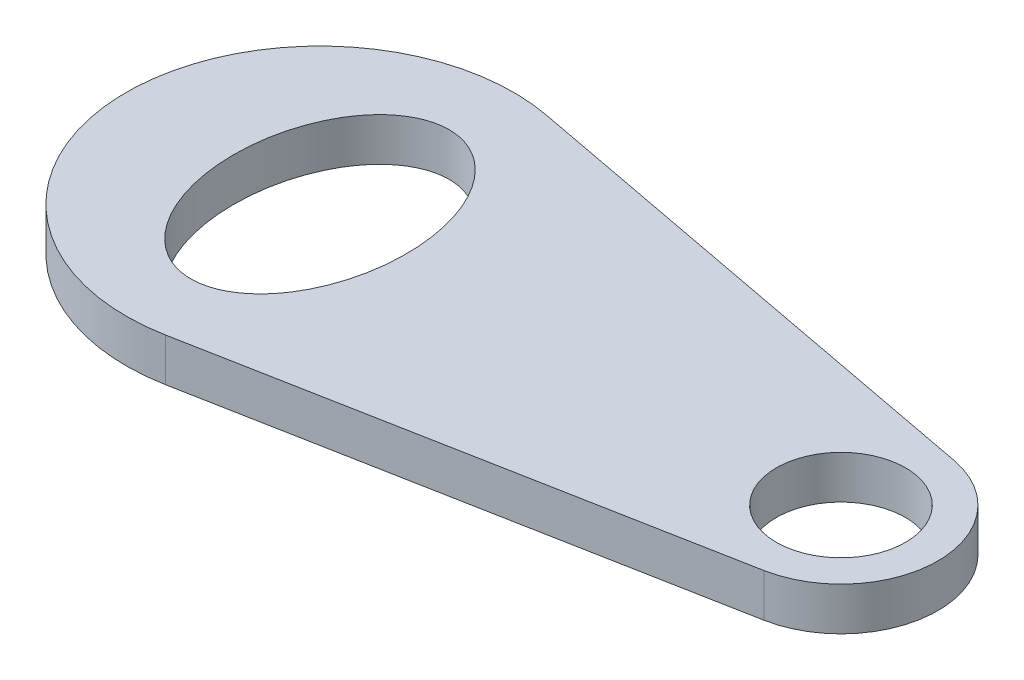
SolidWorks part; units mm, degrees
ref_plane "Front Plane" through (0, 0, 0) normal (0, 0, 1) x (1, 0, 0)
ref_plane "Top Plane" through (0, 0, 0) normal (0, 1, 0) x (1, 0, 0)
ref_plane "Right Plane" through (0, 0, 0) normal (1, 0, 0) x (0, 0, -1)
sketch "Sketch1" plane through (0, 0, 0) normal (0, 1, 0) x (1, 0, 0)
  line L0 (0, 0) -> (-85.6289, 0) construction
  line L1 (0, 0) -> (94.3711, 0) construction
  line L2 (-34.4448, 44.2148) -> (82.3439, 22.1074)
  line L3 (-34.4448, -44.2148) -> (82.3439, -22.1074)
  arc A0 (-34.4448, 44.2148) -> (-34.4448, -44.2148) centre (-42.8144, 0) ccw
  arc A1 (82.3439, -22.1074) -> (82.3439, 22.1074) centre (78.1591, 0) ccw
  circle A2 centre (78.1591, 0) radius 15
  ellipse E0 centre (-42.8144, 0) end of major axis (-42.8144, 30) minor radius 20
  dimension "D1" = 90
  dimension "D3" = 45
  dimension "D4" = 88.4296
  dimension "D5" = 30
  dimension "D2" = 180
extrude "Boss-Extrude1" add sketch "Sketch1" along normal blind 10
